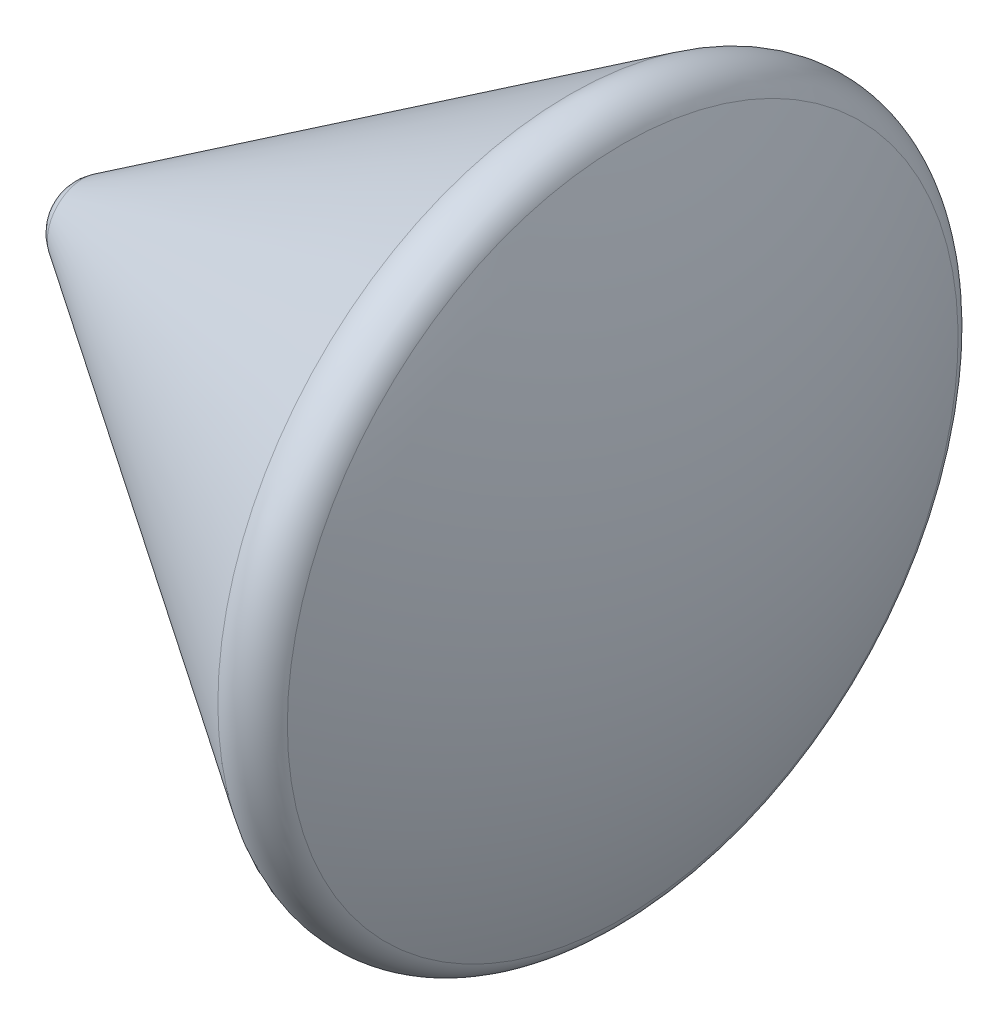
SolidWorks part; units mm, degrees
ref_plane "Piano frontale" through (0, 0, 0) normal (0, 0, 1) x (1, 0, 0)
ref_plane "Piano superiore" through (0, 0, 0) normal (0, 1, 0) x (1, 0, 0)
ref_plane "Piano destro" through (0, 0, 0) normal (1, 0, 0) x (0, 0, -1)
sketch "Schizzo1" plane through (0, 0, 0) normal (0, 0, 1) x (1, 0, 0)
  line L0 (105.1884, 193.7329) -> (2738.3446, 1903.7245)
  line L1 (2845.0938, 1935.3451) -> (2845.0938, 0) construction
  line L2 (0, 0) -> (3391, 0)
  arc A0 (2738.3446, 1903.7245) -> (3025.8467, 1815.1369) centre (2845.0938, 1739.3451) cw
  arc A1 (3025.8467, 1815.1369) -> (3391, 0) centre (-1303, 0) cw
  arc A2 (105.1884, 193.7329) -> (0, 0) centre (231, 0) ccw
  point P8 (0, 0)
  point P9 (4053.8946, -362.5613)
  point P10 (2197.4614, 1817.8982)
  point P11 (2211.7784, 2209.8982)
  point P12 (0, 0)
  dimension "D1" = 231
  dimension "D2" = 196
  dimension "D3" = 4694
  dimension "D4" = 33
  dimension "D5" = 3391
  dimension "D6" = 1935.3451
revolve "Rivoluzione1" add sketch "Schizzo1" angle 360 about L2
